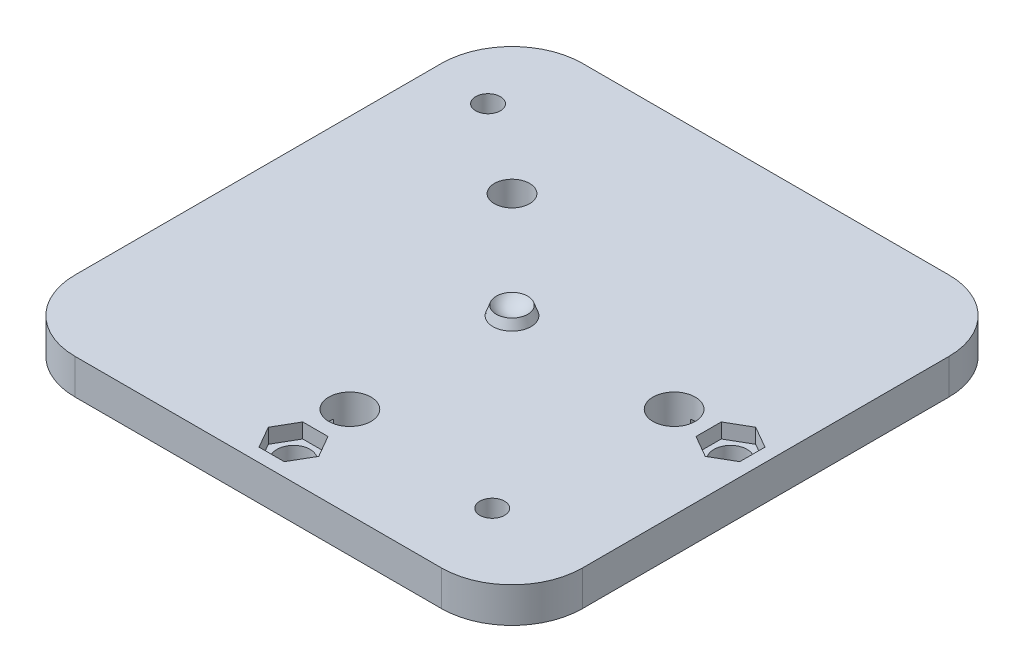
SolidWorks part; units mm, degrees
material "ABS"
ref_plane "Front Plane" through (0, 0, 0) normal (0, 0, 1) x (1, 0, 0)
ref_plane "Top Plane" through (0, 0, 0) normal (0, 1, 0) x (1, 0, 0)
ref_plane "Right Plane" through (0, 0, 0) normal (1, 0, 0) x (0, 0, -1)
sketch "Sketch3" plane through (0, 0, 0) normal (0, 0, 1) x (1, 0, 0)
  line L3 (0, 0) -> (2.7, 0)
  line L4 (0, 0) -> (0, 2.8) construction
  line L5 (2.2332, 1.2825) -> (2.7, 0)
  line L6 (0, 0.1) -> (0, 0)
  arc A1 (0, 0.1) -> (2.2332, 1.2825) centre (0, 2.8) ccw
  dimension "D2" = 2.7
  dimension "D1" = 0.1
  dimension "D4" = 2.7
  dimension "D3" = 70
revolve "Revolve1" add sketch "Sketch3" angle 360 about L6
sketch "Sketch4" plane through (0, 0, 0) normal (0, -1, 0) x (1, 0, 0)
  line L0 (0, 0) -> (-36, 0) construction
  line L1 (-36, -36) -> (36, -36)
  line L2 (-36, -36) -> (-36, 36)
  line L3 (-36, 36) -> (36, 36)
  line L4 (36, -36) -> (36, 36)
  line L5 (-36, -36) -> (36, 36) construction
  line L6 (-36, 36) -> (36, -36) construction
  line L7 (0, 23) -> (0, 0) construction
  line L8 (0, 0) -> (23, 0) construction
  line L9 (0, 0) -> (0, 36) construction
  line L10 (-15, -15) -> (0, -15) construction
  line L11 (-15, -15) -> (-15, 0) construction
  circle A0 centre (23, 0) radius 3
  circle A1 centre (0, 23) radius 3
  circle A2 centre (-15, -15) radius 2.5
  circle A3 centre (0, 31) radius 2.35
  circle A4 centre (31, 0) radius 2.35
  point P0 (0, 0)
  dimension "D3" = 6
  dimension "D4" = 5
  dimension "D6" = 4.7
  dimension "D1" = 36
  dimension "D2" = 23
  dimension "D5" = 15
  dimension "D7" = 8
  dimension "D8" = 8
extrude "Boss-Extrude2" add sketch "Sketch4" along normal blind 5
sketch "Sketch5" plane through (0, -5, 0) normal (0, -1, 0) x (1, 0, 0)
  line L0 (-5.2, 23.6) -> (5.2, 23.6)
  line L1 (5.2, 23.6) -> (5.2, 22.4)
  line L2 (5.2, 22.4) -> (-5.2, 22.4)
  line L3 (-5.2, 22.4) -> (-5.2, 23.6)
  line L4 (22.4, 5.2) -> (23.6, 5.2)
  line L5 (23.6, 5.2) -> (23.6, -5.2)
  line L6 (23.6, -5.2) -> (22.4, -5.2)
  line L7 (22.4, -5.2) -> (22.4, 5.2)
  line L8 (-18.2527, -10.8988) -> (-10.8988, -18.2527)
  line L9 (-10.8988, -18.2527) -> (-11.7473, -19.1012)
  line L10 (-11.7473, -19.1012) -> (-19.1012, -11.7473)
  line L11 (-19.1012, -11.7473) -> (-18.2527, -10.8988)
  line L12 (-15, -15) -> (-15.4243, -15.4243) construction
  line L13 (-15, -15) -> (-14.5757, -14.5757) construction
  line L14 (-15, -15) -> (-18.677, -11.323) construction
  line L15 (-15, -15) -> (-11.323, -18.677) construction
  line L16 (-36, 36) -> (-36, -36) construction
  point P0 (0, 23)
  point P1 (23, 0)
  point P3 (-15, -15)
  point P16 (5.2, 23)
  point P19 (-5.2, 23)
  point P20 (0, 23.6)
  point P21 (0, 22.4)
  point P22 (22.4, 0)
  point P23 (23.6, 0)
  point P24 (23, 5.2)
  point P25 (23, -5.2)
  dimension "D1" = 10.4
  dimension "D2" = 1.2
  dimension "D3" = 135
extrude "Cut-Extrude1" cut sketch "Sketch5" against normal blind 2
sketch "Sketch6" plane through (0, 0, 0) normal (0, 1, 0) x (1, 0, 0)
  line L0 (36, -36) -> (-36, -36) construction
  line L1 (1.7898, -27.9) -> (-1.7898, -27.9)
  line L2 (-1.7898, -27.9) -> (-3.5796, -31)
  line L3 (-3.5796, -31) -> (-1.7898, -34.1)
  line L4 (-1.7898, -34.1) -> (1.7898, -34.1)
  line L5 (1.7898, -34.1) -> (3.5796, -31)
  line L6 (3.5796, -31) -> (1.7898, -27.9)
  line L7 (34.1, 1.7898) -> (31, 3.5796)
  line L8 (31, 3.5796) -> (27.9, 1.7898)
  line L9 (27.9, 1.7898) -> (27.9, -1.7898)
  line L10 (27.9, -1.7898) -> (31, -3.5796)
  line L11 (31, -3.5796) -> (34.1, -1.7898)
  line L12 (34.1, -1.7898) -> (34.1, 1.7898)
  line L13 (36, 36) -> (36, -36) construction
  circle A0 centre (0, -31) radius 3.1 construction
  circle A1 centre (31, 0) radius 3.1 construction
  dimension "D1" = 6.2
extrude "Cut-Extrude2" cut sketch "Sketch6" against normal blind 2.1
fillet "Fillet1" radius 10 4 edges at (-36, -2.5, -36) (36, -2.5, -36) (-36, -2.5, 36) (36, -2.5, 36)
sketch "Sketch7" plane through (0, -5, 0) normal (0, -1, 0) x (1, 0, 0)
  line L0 (36, -26) -> (36, 26) construction
  line L1 (26, 36) -> (-26, 36) construction
  circle A1 centre (22.26, 25.07) radius 1.75
  dimension "D1" = 13.74
  dimension "D3" = 3.5
  dimension "D2" = 10.93
extrude "Cut-Extrude3" cut sketch "Sketch7" against normal up to surface (5 mm away) up to face at (0, 0, 31)
sketch "Sketch8" plane through (0, -5, 0) normal (0, -1, 0) x (1, 0, 0)
  line L0 (-26, -36) -> (26, -36) construction
  line L1 (-36, 26) -> (-36, -26) construction
  circle A1 centre (-27.74, -24.34) radius 1.75
  circle A2 centre (22.26, 25.07) radius 1.75 construction
  dimension "D1" = 11.66
  dimension "D2" = 8.26
extrude "Cut-Extrude4" cut sketch "Sketch8" against normal up to surface (5 mm away) up to face at (22.26, 0, 26.82)
